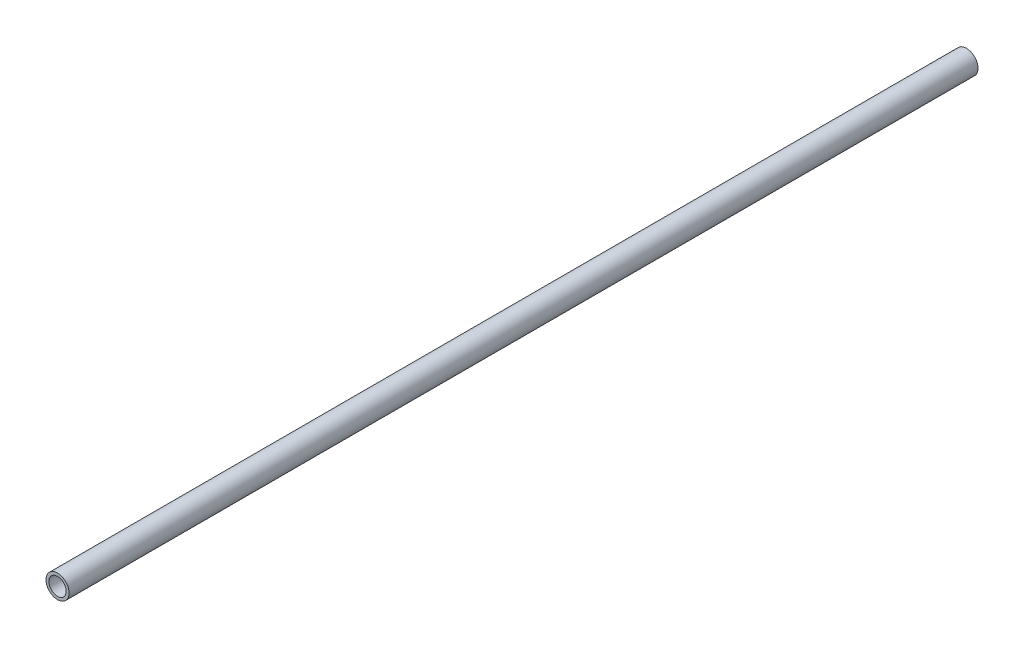
SolidWorks part; units mm, degrees
ref_plane "Front" through (0, 0, 0) normal (0, 0, 1) x (1, 0, 0)
ref_plane "Top" through (0, 0, 0) normal (0, 1, 0) x (1, 0, 0)
ref_plane "Right" through (0, 0, 0) normal (1, 0, 0) x (0, 0, -1)
sketch "Sketch1" plane through (0, 0, 0) normal (0, 0, 1) x (1, 0, 0)
  circle A0 centre (0, 0) radius 4.7625
  circle A1 centre (0, 0) radius 6.35
extrude "Extrude1" add sketch "Sketch1" along normal blind 500
